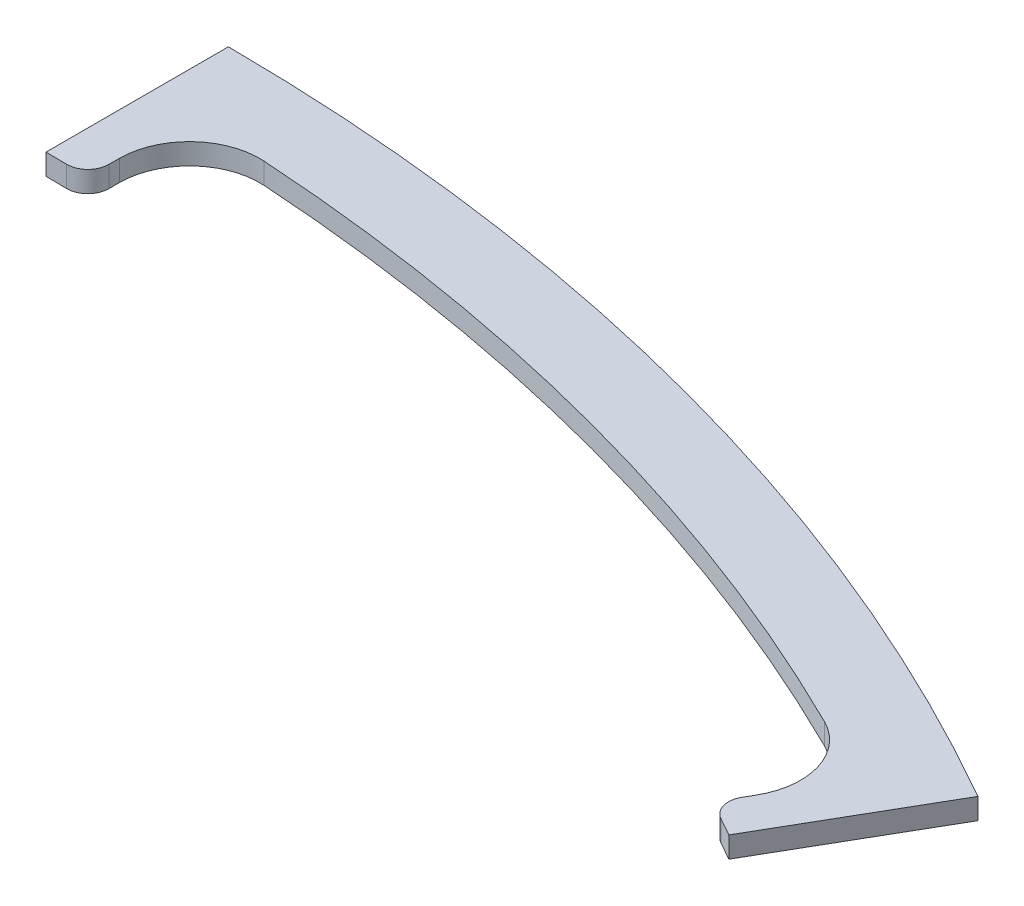
SolidWorks part; units mm, degrees
ref_plane "Front Plane" through (0, 0, 0) normal (0, 0, 1) x (1, 0, 0)
ref_plane "Top Plane" through (0, 0, 0) normal (0, 1, 0) x (1, 0, 0)
ref_plane "Right Plane" through (0, 0, 0) normal (1, 0, 0) x (0, 0, -1)
sketch "Sketch1" plane through (0, 0, 0) normal (0, 1, 0) x (1, 0, 0)
  line L0 (0, 0) -> (0, 297.5) construction
  line L1 (0, 0) -> (148.75, 257.6426) construction
  line L2 (204.8954, 357.8892) -> (-50.4142, -84.3199) construction
  line L3 (1.5, 359.3331) -> (1.5, -61.2496) construction
  line L4 (1.5, 297.4962) -> (1.5, 271.4962)
  line L5 (147.4491, 258.3893) -> (134.4491, 235.8726)
  circle A0 centre (0, 0) radius 297.5 construction
  arc A1 (1.5, 297.4962) -> (147.4491, 258.3893) centre (0, 0) cw
  arc A3 (1.5, 271.4962) -> (134.4491, 235.8726) centre (0, 0) cw
  point P12 (0, 0)
  point P13 (3.1922, 271.4962)
  point P15 (0, 0)
  dimension "D1" = 595
  dimension "D5" = 26
  dimension "D2" = 30
  dimension "D3" = 1.5
  dimension "D4" = 1.5
extrude "Boss-Extrude1" add sketch "Sketch1" along normal blind 3
sketch "Sketch3" plane through (0, 3, 0) normal (0, 1, 0) x (1, 0, 0)
  line L0 (7.5, 271.3968) -> (129.2032, 238.7865)
  line L3 (7.5, 297.4962) -> (7.5, 271.4962)
  line L4 (7.5, 286.4022) -> (7.5, 271.3968)
  line L8 (129.2529, 238.8726) -> (142.2529, 261.3893)
  line L9 (129.2032, 238.7865) -> (136.7059, 251.7816)
  arc A0 (134.4491, 235.8726) -> (1.5, 271.4962) centre (0, 0) ccw construction
  arc A1 (134.4491, 235.8726) -> (1.5, 271.4962) centre (0, 0) ccw construction
  arc A3 (141.8772, 248.9042) -> (1.5829, 286.496) centre (0, 0) ccw
  arc A4 (136.7059, 251.7816) -> (7.5, 286.4022) centre (0, 0) ccw
  point P0 (129.0599, 238.5383)
  dimension "D1" = 15
  dimension "D2" = 6
  dimension "D3" = 6
extrude "Cut-Extrude1" cut sketch "Sketch3" against normal blind 3
fillet "Fillet1" radius 10 2 edges at (7.5, 1.5, -286.4022) (136.7059, 1.5, -251.7816)
fillet "Fillet2" radius 3 2 edges at (129.2032, 1.5, -238.7865) (7.5, 1.5, -271.3968)
